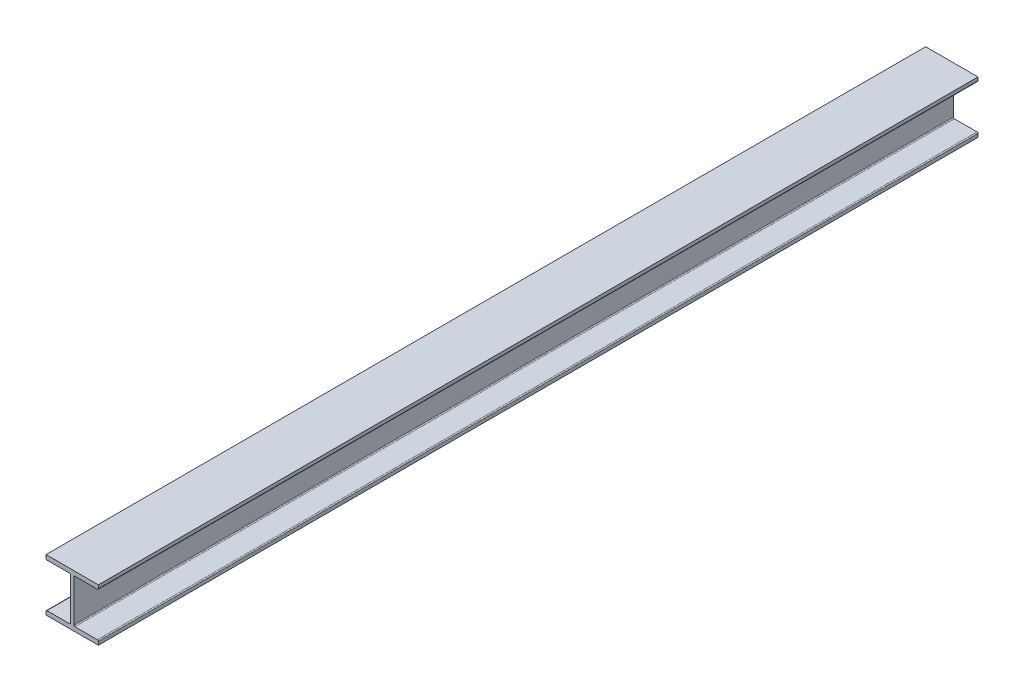
SolidWorks part; units mm, degrees
material "6061 Alloy"
ref_plane "Front Plane" through (0, 0, 0) normal (0, 0, 1) x (1, 0, 0)
ref_plane "Top Plane" through (0, 0, 0) normal (0, 1, 0) x (1, 0, 0)
ref_plane "Right Plane" through (0, 0, 0) normal (1, 0, 0) x (0, 0, -1)
sketch "Sketch1" plane through (0, 0, 0) normal (0, 0, 1) x (1, 0, 0)
  line L0 (0, 63.5) -> (0, -63.5) construction
  line L1 (-63.5, 63.5) -> (63.5, 63.5)
  line L2 (63.5, 63.5) -> (63.5, 53.0352)
  line L3 (63.5, 53.0352) -> (23.0251, 53.0352)
  line L4 (3.9751, 33.9852) -> (3.9751, -53.0352)
  line L5 (3.9751, -53.0352) -> (63.5, -53.0352)
  line L6 (63.5, -53.0352) -> (63.5, -63.5)
  line L7 (63.5, -63.5) -> (-63.5, -63.5)
  line L8 (-63.5, -53.0352) -> (-63.5, -63.5)
  line L9 (-3.9751, -53.0352) -> (-63.5, -53.0352)
  line L10 (-3.9751, 33.9852) -> (-3.9751, -53.0352)
  line L11 (-63.5, 53.0352) -> (-23.0251, 53.0352)
  line L12 (-63.5, 63.5) -> (-63.5, 53.0352)
  line L13 (-23.0251, 53.0352) -> (-23.0251, 33.9852)
  line L14 (-23.0251, 33.9852) -> (-3.9751, 33.9852)
  line L15 (23.0251, 53.0352) -> (23.0251, 33.9852)
  line L16 (23.0251, 33.9852) -> (3.9751, 33.9852)
  dimension "D1" = 127
  dimension "D2" = 10.4648
  dimension "D3" = 127
  dimension "D4" = 7.9502
  dimension "D5" = 127
  dimension "D6" = 19.05
  dimension "D7" = 19.05
  dimension "D8" = 19.05
extrude "Boss-Extrude1" add sketch "Sketch1" along normal blind 2133.6
sketch "Sketch2" plane through (0, 0, 0) normal (0, 0, 1) x (1, 0, 0)
  line L0 (-3.9751, 33.9852) -> (-3.9751, 53.0352)
  line L1 (-3.9751, 53.0352) -> (-23.0251, 53.0352)
  line L2 (-23.0251, 53.0352) -> (-23.0251, 33.9852)
  line L3 (-23.0251, 33.9852) -> (-3.9751, 33.9852)
  line L4 (3.9751, 33.9852) -> (3.9751, 53.0352)
  line L5 (3.9751, 53.0352) -> (23.0251, 53.0352)
  line L6 (23.0251, 53.0352) -> (23.0251, 33.9852)
  line L7 (23.0251, 33.9852) -> (3.9751, 33.9852)
extrude "Cut-Extrude1" cut sketch "Sketch2" along normal through all
fillet "Fillet1" radius 2.54 8 edges at (63.5, -53.0352, 1066.8) (-63.5, -53.0352, 1066.8) (-63.5, 53.0352, 1066.8) (63.5, 53.0352, 1066.8) (3.9751, 53.0352, 1066.8) (-3.9751, 53.0352, 1066.8) (3.9751, -53.0352, 1066.8) (-3.9751, -53.0352, 1066.8)
equation "\"D1@Boss-Extrude1\"=7*12"
